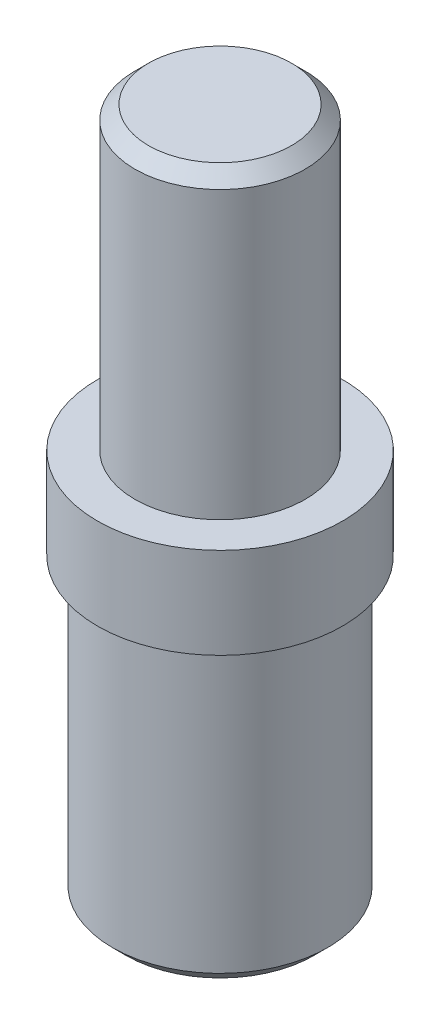
SolidWorks part; units mm, degrees
ref_plane "Front Plane" through (0, 0, 0) normal (0, 0, 1) x (1, 0, 0)
ref_plane "Top Plane" through (0, 0, 0) normal (0, 1, 0) x (1, 0, 0)
ref_plane "Right Plane" through (0, 0, 0) normal (1, 0, 0) x (0, 0, -1)
sketch "Sketch1" plane through (0, 0, 0) normal (0, 1, 0) x (1, 0, 0)
  circle A0 centre (0, 0) radius 3.95
  dimension "D1" = 7.9
extrude "Boss-Extrude1" add sketch "Sketch1" along normal blind 11
sketch "Sketch2" plane through (0, 11, 0) normal (0, 1, 0) x (1, 0, 0)
  circle A0 centre (0, 0) radius 4.5
  dimension "D1" = 9
extrude "Boss-Extrude2" add sketch "Sketch2" along normal blind 3.34
sketch "Sketch4" plane through (0, 14.34, 0) normal (0, 1, 0) x (1, 0, 0)
  circle A0 centre (0, 0) radius 3.125
  dimension "D1" = 6.25
extrude "Boss-Extrude3" add sketch "Sketch4" along normal blind 11
chamfer "Chamfer1" distance 0.5 angle 45 2 edges at (0, 0, 3.95) (0, 25.34, 3.125)
sketch "Sketch5" plane through (0, 0, 0) normal (0, -1, 0) x (1, 0, 0)
  circle A0 centre (0, 0) radius 1.5
  dimension "D1" = 3
extrude "Cut-Extrude1" [suppressed] cut sketch "Sketch5" against normal through all
